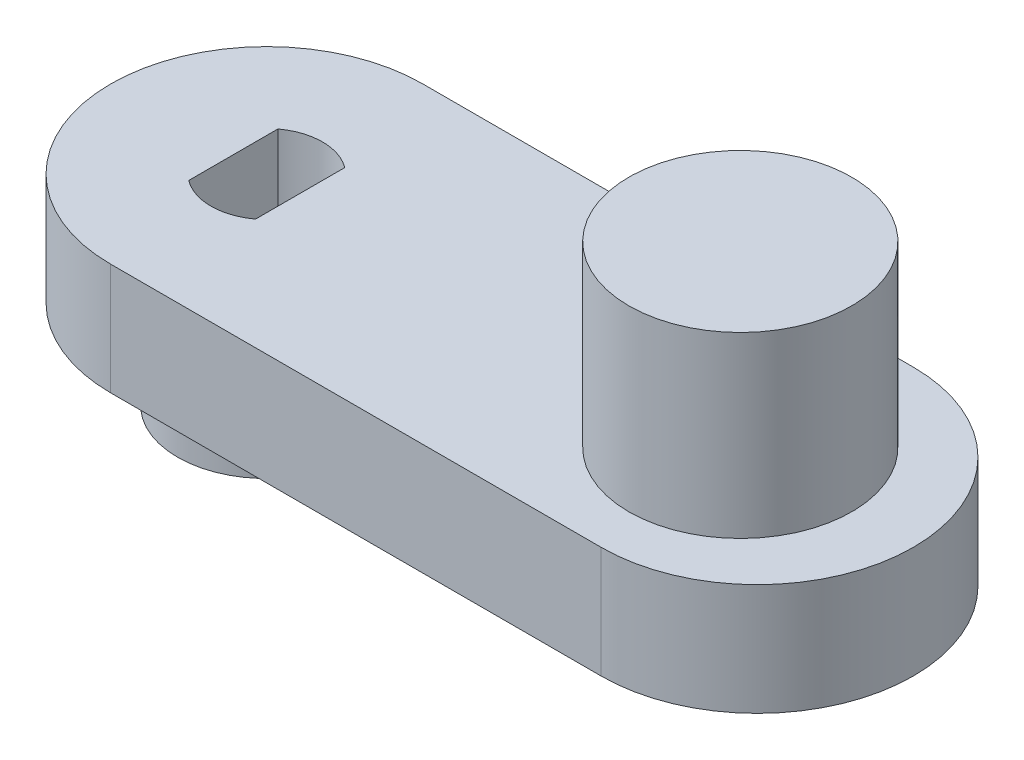
SolidWorks part; units mm, degrees
ref_plane "Front Plane" through (0, 0, 0) normal (0, 0, 1) x (1, 0, 0)
ref_plane "Top Plane" through (0, 0, 0) normal (0, 1, 0) x (1, 0, 0)
ref_plane "Right Plane" through (0, 0, 0) normal (1, 0, 0) x (0, 0, -1)
sketch "Sketch1" plane through (0, 0, 0) normal (0, 1, 0) x (1, 0, 0)
  line L0 (0, 0) -> (22, 0) construction
  line L1 (0, 7) -> (22, 7)
  line L2 (0, -7) -> (22, -7)
  arc A0 (0, 7) -> (0, -7) centre (0, 0) ccw
  arc A1 (22, -7) -> (22, 7) centre (22, 0) ccw
  point P3 (11, 0)
  dimension "D1" = 36
  dimension "D2" = 14
extrude "Boss-Extrude1" add sketch "Sketch1" along normal blind 5
sketch "Sketch2" plane through (0, 5, 0) normal (0, 1, 0) x (1, 0, 0)
  line L0 (1.5, 2) -> (1.5, -2)
  line L1 (-1.5, 2) -> (-1.5, -2)
  arc A0 (1.5, 2) -> (-1.5, 2) centre (0, 0) ccw
  arc A2 (-1.5, -2) -> (1.5, -2) centre (0, 0) ccw
  dimension "D1" = 5
  dimension "D2" = 1
  dimension "D3" = 1
extrude "Cut-Extrude1" cut sketch "Sketch2" against normal up to surface (5 mm away) up to face at (11, 0, 0)
sketch "Sketch3" plane through (0, 5, 0) normal (0, 1, 0) x (1, 0, 0)
  line L2 (1.5, -2) -> (1.5, 2) construction
  circle A0 centre (21.24, 0) radius 5
  dimension "D1" = 10
  dimension "D2" = 14.74
extrude "Boss-Extrude2" add sketch "Sketch3" along normal blind 8
sketch "Sketch5" plane through (0, 0, 0) normal (0, -1, 0) x (1, 0, 0)
  line L0 (-1.5, 2) -> (-1.5, -2) construction
  line L1 (1.5, -2) -> (1.5, 2) construction
  line L2 (-1.5, 2) -> (-1.5, -2)
  line L3 (1.5, -2) -> (1.5, 2)
  arc A0 (-1.5, -2) -> (1.5, -2) centre (0, 0) ccw construction
  arc A1 (1.5, 2) -> (-1.5, 2) centre (0, 0) ccw construction
  arc A2 (-1.5, -2) -> (1.5, -2) centre (0, 0) ccw
  arc A3 (1.5, 2) -> (-1.5, 2) centre (0, 0) ccw
  circle A4 centre (0, 0) radius 4
  dimension "D1" = 8
extrude "Boss-Extrude4" add sketch "Sketch5" along normal blind 4
